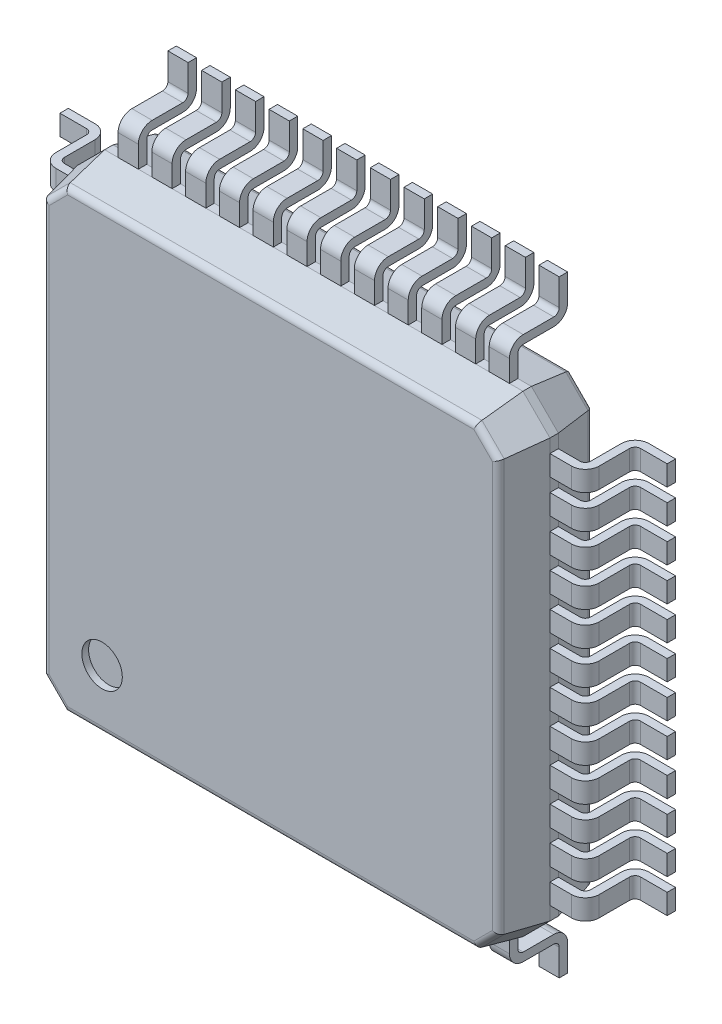
SolidWorks part; units mm, degrees
ref_plane "Front Plane" through (0, 0, 0) normal (0, 0, 1) x (1, 0, 0)
ref_plane "Top Plane" through (0, 0, 0) normal (0, 1, 0) x (1, 0, 0)
ref_plane "Right Plane" through (0, 0, 0) normal (1, 0, 0) x (0, 0, -1)
ref_plane "Plane1" through (0, 0, 0.1) normal (0, 0, 1) x (1, 0, 0)
sketch "Sketch1" plane through (0, 0, 0.1) normal (0, 0, 1) x (1, 0, 0)
  line L0 (-3.1, 3.5) -> (-3.5, 3.1)
  line L1 (-3.1, 3.5) -> (3.1, 3.5)
  line L2 (-3.5, 3.1) -> (-3.5, -3.1)
  line L3 (-3.1, -3.5) -> (3.1, -3.5)
  line L4 (3.5, 3.1) -> (3.5, -3.1)
  line L5 (-3.5, -3.1) -> (-3.1, -3.5)
  line L6 (3.1, -3.5) -> (3.5, -3.1)
  line L7 (3.1, 3.5) -> (3.5, 3.1)
extrude "Extrude1" add sketch "Sketch1" along normal blind 1.4
chamfer "Chamfer1" distance 0.6375 angle 12 16 edges at (-3.3, 3.3, 1.5) (0, 3.5, 1.5) (3.3, 3.3, 1.5) (3.5, 0, 1.5) (3.3, -3.3, 1.5) (0, -3.5, 1.5) (-3.3, -3.3, 1.5) (-3.5, 0, 1.5) (-3.3, -3.3, 0.1) (0, -3.5, 0.1) (3.3, -3.3, 0.1) (3.5, 0, 0.1) (3.3, 3.3, 0.1) (0, 3.5, 0.1) (-3.3, 3.3, 0.1) (-3.5, 0, 0.1)
fillet "Fillet1" radius 0.1 16 edges at (3.2042, 3.2042, 1.5) (3.3645, 0, 1.5) (3.2042, -3.2042, 1.5) (0, -3.3645, 1.5) (-3.2042, -3.2042, 1.5) (-3.3645, 0, 1.5) (-3.2042, 3.2042, 1.5) (0, 3.3645, 1.5) (3.2042, -3.2042, 0.1) (3.3645, 0, 0.1) (3.2042, 3.2042, 0.1) (0, 3.3645, 0.1) (-3.2042, 3.2042, 0.1) (-3.3645, 0, 0.1) (-3.2042, -3.2042, 0.1) (0, -3.3645, 0.1)
sketch "Sketch2" plane through (0, 0, 0) normal (0, 0, 1) x (1, 0, 0)
  line L0 (2.1, -3.5) -> (2.1, -4.5)
  line L2 (2.6, -3.5) -> (2.9, -3.5)
  line L3 (2.6, -3.5) -> (2.6, -4.5)
  line L4 (2.6, -4.5) -> (2.9, -4.5)
  line L5 (2.9, -3.5) -> (2.9, -4.5)
  line L6 (2.4, -3.5) -> (2.4, -4.5)
  line L7 (2.1, -3.5) -> (2.4, -3.5)
  line L8 (2.1, -4.5) -> (2.4, -4.5)
  line L9 (1.6, -3.5) -> (1.6, -4.5)
  line L10 (1.9, -3.5) -> (1.9, -4.5)
  line L11 (1.6, -3.5) -> (1.9, -3.5)
  line L12 (1.6, -4.5) -> (1.9, -4.5)
  line L13 (1.1, -3.5) -> (1.1, -4.5)
  line L14 (1.4, -3.5) -> (1.4, -4.5)
  line L15 (1.1, -3.5) -> (1.4, -3.5)
  line L16 (1.1, -4.5) -> (1.4, -4.5)
  line L17 (0.6, -3.5) -> (0.6, -4.5)
  line L18 (0.9, -3.5) -> (0.9, -4.5)
  line L19 (0.6, -3.5) -> (0.9, -3.5)
  line L20 (0.6, -4.5) -> (0.9, -4.5)
  line L21 (0.1, -3.5) -> (0.1, -4.5)
  line L22 (0.4, -3.5) -> (0.4, -4.5)
  line L23 (0.1, -3.5) -> (0.4, -3.5)
  line L24 (0.1, -4.5) -> (0.4, -4.5)
  line L25 (-0.4, -3.5) -> (-0.4, -4.5)
  line L26 (-0.1, -3.5) -> (-0.1, -4.5)
  line L27 (-0.4, -3.5) -> (-0.1, -3.5)
  line L28 (-0.4, -4.5) -> (-0.1, -4.5)
  line L29 (-0.9, -3.5) -> (-0.9, -4.5)
  line L30 (-0.6, -3.5) -> (-0.6, -4.5)
  line L31 (-0.9, -3.5) -> (-0.6, -3.5)
  line L32 (-0.9, -4.5) -> (-0.6, -4.5)
  line L33 (-1.4, -3.5) -> (-1.4, -4.5)
  line L34 (-1.1, -3.5) -> (-1.1, -4.5)
  line L35 (-1.4, -3.5) -> (-1.1, -3.5)
  line L36 (-1.4, -4.5) -> (-1.1, -4.5)
  line L37 (-1.9, -3.5) -> (-1.9, -4.5)
  line L38 (-1.6, -3.5) -> (-1.6, -4.5)
  line L39 (-1.9, -3.5) -> (-1.6, -3.5)
  line L40 (-1.9, -4.5) -> (-1.6, -4.5)
  line L41 (-2.4, -3.5) -> (-2.4, -4.5)
  line L42 (-2.1, -3.5) -> (-2.1, -4.5)
  line L43 (-2.4, -3.5) -> (-2.1, -3.5)
  line L44 (-2.4, -4.5) -> (-2.1, -4.5)
  line L45 (-2.9, -3.5) -> (-2.9, -4.5)
  line L46 (-2.6, -3.5) -> (-2.6, -4.5)
  line L47 (-2.9, -3.5) -> (-2.6, -3.5)
  line L48 (-2.9, -4.5) -> (-2.6, -4.5)
extrude "Extrude2" add sketch "Sketch2" along normal blind 0.8625
sketch "Sketch3" plane through (2.9, 0, 0) normal (1, 0, 0) x (0, 0, -1)
  line L0 (-0.6575, -3.9) -> (-0.205, -3.9)
  line L1 (-0.8625, -3.82) -> (-0.8625, -4.5)
  line L2 (-0.8625, -4.5) -> (-0.125, -4.5)
  line L3 (-0.7375, -3.5) -> (0, -3.5)
  line L4 (-0.7375, -3.5) -> (-0.7375, -3.82)
  line L5 (0, -3.5) -> (0, -4.105)
  line L6 (-0.125, -4.105) -> (-0.125, -4.5)
  line L7 (-0.6575, -4.025) -> (-0.205, -4.025)
  line L8 (-0.8625, -4.5) -> (0, -4.5) construction
  arc A0 (-0.7375, -3.82) -> (-0.6575, -3.9) centre (-0.6575, -3.82) ccw
  arc A1 (-0.8625, -3.82) -> (-0.6575, -4.025) centre (-0.6575, -3.82) ccw
  arc A2 (-0.125, -4.105) -> (-0.205, -4.025) centre (-0.205, -4.105) ccw
  arc A3 (0, -4.105) -> (-0.205, -3.9) centre (-0.205, -4.105) ccw
extrude "Extrude3" cut sketch "Sketch3" against normal through all
mirror "Mirror1" about plane through (0, 0, 0) normal (0, 1, 0) of "Extrude3", "Extrude2"
sketch "Sketch4" plane through (0, 0, 0) normal (0, 0, 1) x (1, 0, 0)
  line L1 (-3.5, -2.1) -> (-4.5, -2.1)
  line L2 (-4.5, -2.1) -> (-4.5, -2.4)
  line L3 (-3.5, -2.4) -> (-4.5, -2.4)
  line L4 (-3.5, -2.1) -> (-3.5, -2.4)
  line L5 (-3.5, -1.6) -> (-4.5, -1.6)
  line L6 (-4.5, -1.6) -> (-4.5, -1.9)
  line L7 (-3.5, -1.9) -> (-4.5, -1.9)
  line L8 (-3.5, -1.6) -> (-3.5, -1.9)
  line L9 (-3.5, -1.1) -> (-4.5, -1.1)
  line L10 (-4.5, -1.1) -> (-4.5, -1.4)
  line L11 (-3.5, -1.4) -> (-4.5, -1.4)
  line L12 (-3.5, -1.1) -> (-3.5, -1.4)
  line L13 (-3.5, -0.6) -> (-4.5, -0.6)
  line L14 (-4.5, -0.6) -> (-4.5, -0.9)
  line L15 (-3.5, -0.9) -> (-4.5, -0.9)
  line L16 (-3.5, -0.6) -> (-3.5, -0.9)
  line L17 (-3.5, -0.1) -> (-4.5, -0.1)
  line L18 (-4.5, -0.1) -> (-4.5, -0.4)
  line L19 (-3.5, -0.4) -> (-4.5, -0.4)
  line L20 (-3.5, -0.1) -> (-3.5, -0.4)
  line L21 (-3.5, 0.4) -> (-4.5, 0.4)
  line L22 (-4.5, 0.4) -> (-4.5, 0.1)
  line L23 (-3.5, 0.1) -> (-4.5, 0.1)
  line L24 (-3.5, 0.4) -> (-3.5, 0.1)
  line L25 (-3.5, 0.9) -> (-4.5, 0.9)
  line L26 (-4.5, 0.9) -> (-4.5, 0.6)
  line L27 (-3.5, 0.6) -> (-4.5, 0.6)
  line L28 (-3.5, 0.9) -> (-3.5, 0.6)
  line L29 (-3.5, 1.4) -> (-4.5, 1.4)
  line L30 (-4.5, 1.4) -> (-4.5, 1.1)
  line L31 (-3.5, 1.1) -> (-4.5, 1.1)
  line L32 (-3.5, 1.4) -> (-3.5, 1.1)
  line L33 (-3.5, 1.9) -> (-4.5, 1.9)
  line L34 (-4.5, 1.9) -> (-4.5, 1.6)
  line L35 (-3.5, 1.6) -> (-4.5, 1.6)
  line L36 (-3.5, 1.9) -> (-3.5, 1.6)
  line L37 (-3.5, 2.4) -> (-4.5, 2.4)
  line L38 (-4.5, 2.4) -> (-4.5, 2.1)
  line L39 (-3.5, 2.1) -> (-4.5, 2.1)
  line L40 (-3.5, 2.4) -> (-3.5, 2.1)
  line L41 (-3.5, -2.6) -> (-4.5, -2.6)
  line L42 (-4.5, -2.6) -> (-4.5, -2.9)
  line L43 (-3.5, -2.9) -> (-4.5, -2.9)
  line L44 (-3.5, -2.6) -> (-3.5, -2.9)
  line L45 (-3.5, 2.9) -> (-4.5, 2.9)
  line L46 (-4.5, 2.9) -> (-4.5, 2.6)
  line L47 (-3.5, 2.6) -> (-4.5, 2.6)
  line L48 (-3.5, 2.9) -> (-3.5, 2.6)
extrude "Extrude4" add sketch "Sketch4" along normal blind 0.8625
sketch "Sketch5" plane through (0, -2.9, 0) normal (0, -1, 0) x (1, 0, 0)
  line L0 (-3.9, 0.6575) -> (-3.9, 0.205)
  line L4 (-3.5, 0.7375) -> (-3.82, 0.7375)
  line L6 (-4.5, 0.125) -> (-4.105, 0.125)
  line L7 (-4.5, 0.8625) -> (-4.5, 0) construction
  line L8 (-4.025, 0.6575) -> (-4.025, 0.205)
  line L9 (-3.5, 0.7375) -> (-3.5, 0)
  line L10 (-3.5, 0) -> (-4.105, 0)
  line L11 (-3.82, 0.8625) -> (-4.5, 0.8625)
  line L12 (-4.5, 0.8625) -> (-4.5, 0.125)
  arc A0 (-3.82, 0.7375) -> (-3.9, 0.6575) centre (-3.82, 0.6575) ccw
  arc A1 (-3.82, 0.8625) -> (-4.025, 0.6575) centre (-3.82, 0.6575) ccw
  arc A2 (-4.025, 0.205) -> (-4.105, 0.125) centre (-4.105, 0.205) cw
  arc A3 (-3.9, 0.205) -> (-4.105, 0) centre (-4.105, 0.205) cw
extrude "Extrude5" cut sketch "Sketch5" against normal through all
mirror "Mirror2" about plane through (0, 0, 0) normal (1, 0, 0) of "Extrude5", "Extrude4"
sketch "Sketch6" plane through (0, 0, 1.5) normal (0, 0, 1) x (1, 0, 0)
  line L0 (-2.5, -3.5) -> (-2.5, -2.5) construction
  line L2 (-3.5, -2.5) -> (-2.5, -2.5) construction
  line L5 (-2.4, -3.5) -> (-2.6, -3.5) construction
  line L6 (-3.5, -2.6) -> (-3.5, -2.4) construction
  circle A0 centre (-2.5, -2.5) radius 0.3
extrude "Extrude6" cut sketch "Sketch6" against normal blind 0.1
